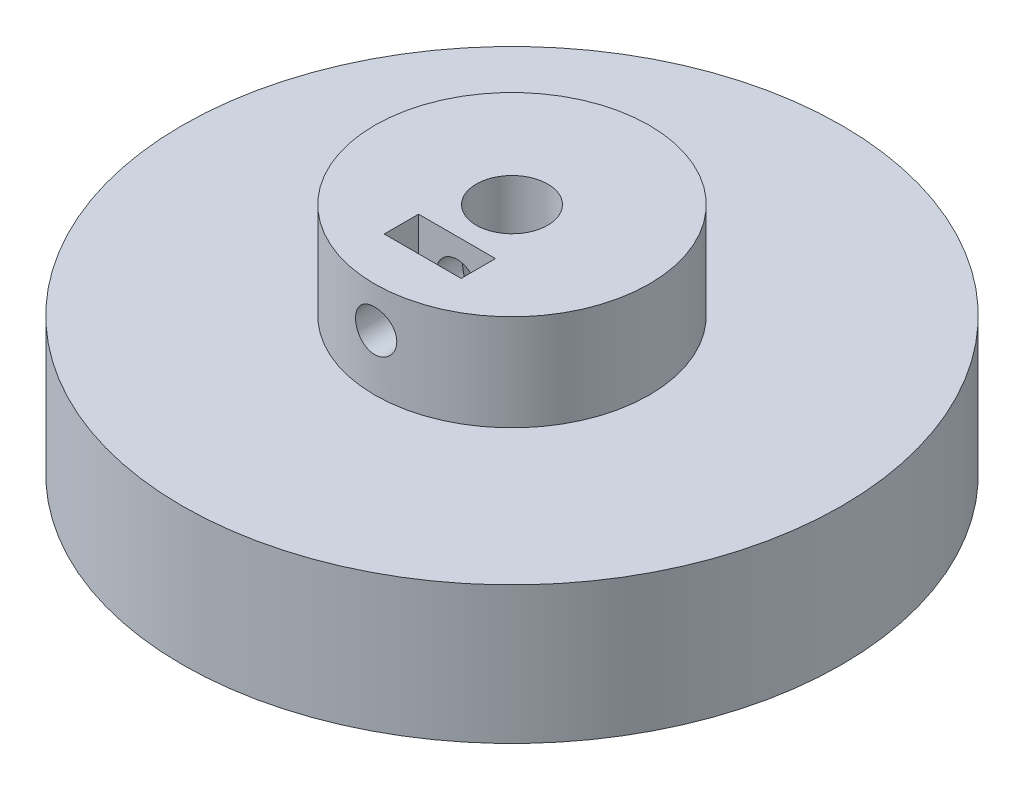
SolidWorks part; units mm, degrees
ref_plane "Front Plane" through (0, 0, 0) normal (0, 0, 1) x (1, 0, 0)
ref_plane "Top Plane" through (0, 0, 0) normal (0, 1, 0) x (1, 0, 0)
ref_plane "Right Plane" through (0, 0, 0) normal (1, 0, 0) x (0, 0, -1)
sketch "PullyBody" plane through (0, 0, 0) normal (0, 1, 0) x (1, 0, 0)
  circle A0 centre (0, 0) radius 24
  circle A1 centre (0, 0) radius 2.6
  dimension "D1" = 48
  dimension "D2" = 5.2
extrude "Boss-Extrude1" add sketch "PullyBody" along normal blind 10
sketch "Sketch2" plane through (0, 10, 0) normal (0, 1, 0) x (1, 0, 0)
  circle A0 centre (0, 0) radius 2.6
  circle A1 centre (0, 0) radius 10
  dimension "D1" = 20
extrude "Boss-Extrude2" add sketch "Sketch2" along normal blind 7
sketch "Sketch3" plane through (0, 17, 0) normal (0, 1, 0) x (1, 0, 0)
  line L0 (0, 0) -> (0, -12.9) construction
  line L2 (-2.8, -4) -> (2.8, -4)
  line L3 (-2.8, -4) -> (-2.8, -6.5)
  line L4 (-2.8, -6.5) -> (2.8, -6.5)
  line L5 (2.8, -4) -> (2.8, -6.5)
  circle A0 centre (0, 0) radius 2.6 construction
  point P2 (0, -4)
  dimension "D1" = 2.5
  dimension "D2" = 5.6
  dimension "D3" = 4
extrude "Cut-Extrude1" cut sketch "Sketch3" against normal blind 5.6
sketch "Sketch4" plane through (0, 0, 0) normal (0, 0, 1) x (1, 0, 0)
  line L0 (2.8, 11.4) -> (-2.8, 11.4) construction
  circle A0 centre (0, 14.05) radius 1.5
  dimension "D1" = 3
  dimension "D2" = 2.65
extrude "Cut-Extrude2" cut sketch "Sketch4" along normal through all
